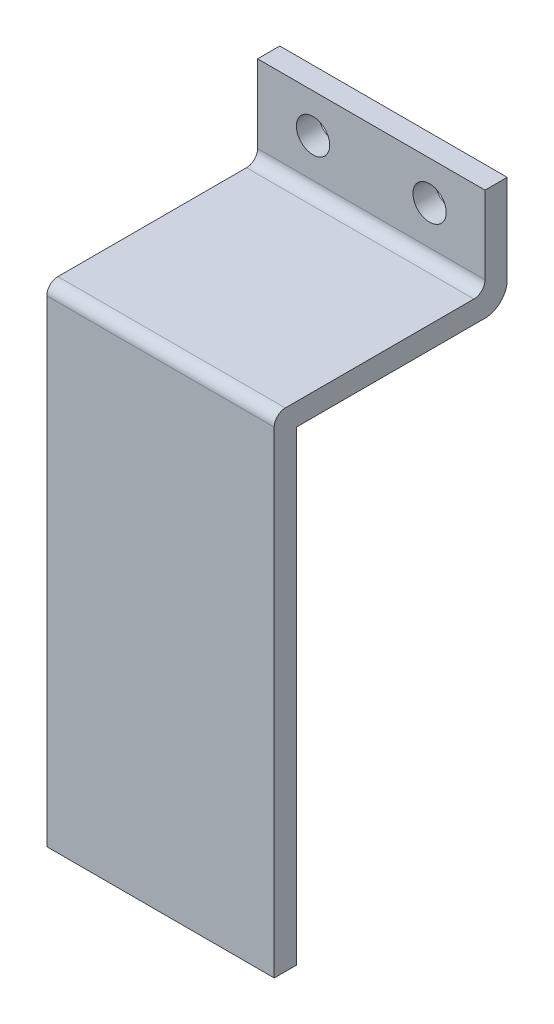
SolidWorks part; units mm, degrees
ref_plane "Front Plane" through (0, 0, 0) normal (0, 0, 1) x (1, 0, 0)
ref_plane "Top Plane" through (0, 0, 0) normal (0, 1, 0) x (1, 0, 0)
ref_plane "Right Plane" through (0, 0, 0) normal (1, 0, 0) x (0, 0, -1)
sketch "Sketch1" plane through (0, 0, 0) normal (1, 0, 0) x (0, 0, -1)
  line L0 (0, 0) -> (0, 43)
  line L1 (1, 44) -> (18, 44)
  line L2 (19, 45) -> (19, 52)
  line L3 (0, 0) -> (0, 44) construction
  line L4 (2, 0) -> (2, 42)
  line L5 (2, 42) -> (19, 42)
  line L6 (21, 44) -> (21, 52)
  line L7 (0, 0) -> (2, 0)
  line L8 (19, 52) -> (21, 52)
  line L9 (0, 44) -> (19, 44) construction
  line L10 (19, 44) -> (19, 52) construction
  line L11 (2, 42) -> (21, 42) construction
  line L12 (21, 42) -> (21, 52) construction
  arc A0 (0, 43) -> (1, 44) centre (1, 43) cw
  arc A1 (18, 44) -> (19, 45) centre (18, 45) ccw
  arc A2 (19, 42) -> (21, 44) centre (19, 44) ccw
  point P18 (21, 42)
  dimension "D5" = 1
  dimension "D6" = 1
  dimension "D7" = 2
  dimension "D1" = 2
  dimension "D2" = 42
  dimension "D3" = 10
  dimension "D4" = 19
extrude "Boss-Extrude1" add sketch "Sketch1" along normal blind 20.5 contours L1 A1 L2 L8 L6 A2 L5 L4 L7 L0 A0
sketch "Sketch2" plane through (0, 0, -19) normal (0, 0, 1) x (1, 0, 0)
  line L0 (10.25, 52) -> (10.25, 45) construction
  line L1 (20.5, 52) -> (0, 52) construction
  line L2 (20.5, 45) -> (0, 45) construction
  line L3 (5, 48.5) -> (10.25, 48.5) construction
  line L4 (0, 45) -> (0, 52) construction
  circle A0 centre (5, 48.5) radius 1.5
  circle A1 centre (15.5, 48.5) radius 1.5
  dimension "D1" = 3
  dimension "D2" = 5
extrude "Cut-Extrude1" cut sketch "Sketch2" against normal through all
